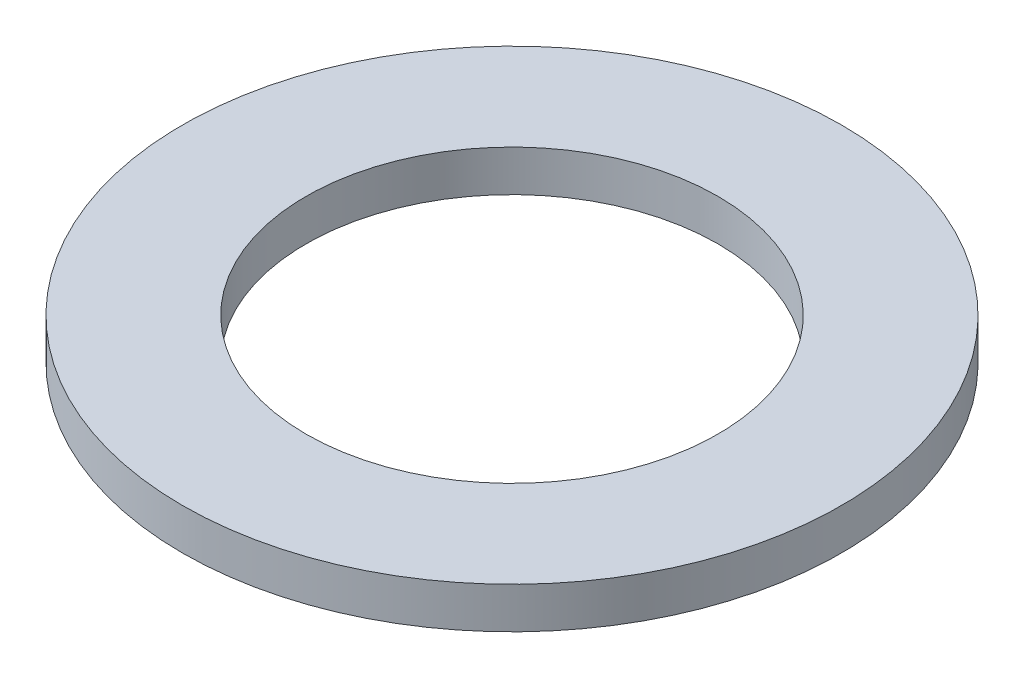
SolidWorks part; units mm, degrees
ref_plane "前视基准面" through (0, 0, 0) normal (0, 0, 1) x (1, 0, 0)
ref_plane "上视基准面" through (0, 0, 0) normal (0, 1, 0) x (1, 0, 0)
ref_plane "右视基准面" through (0, 0, 0) normal (1, 0, 0) x (0, 0, -1)
sketch "草图1" plane through (0, 0, 0) normal (0, 1, 0) x (1, 0, 0)
  circle A0 centre (0, 0) radius 5
  circle A1 centre (0, 0) radius 8
  dimension "D1" = 10
  dimension "D2" = 16
extrude "凸台-拉伸1" add sketch "草图1" along normal blind 1
